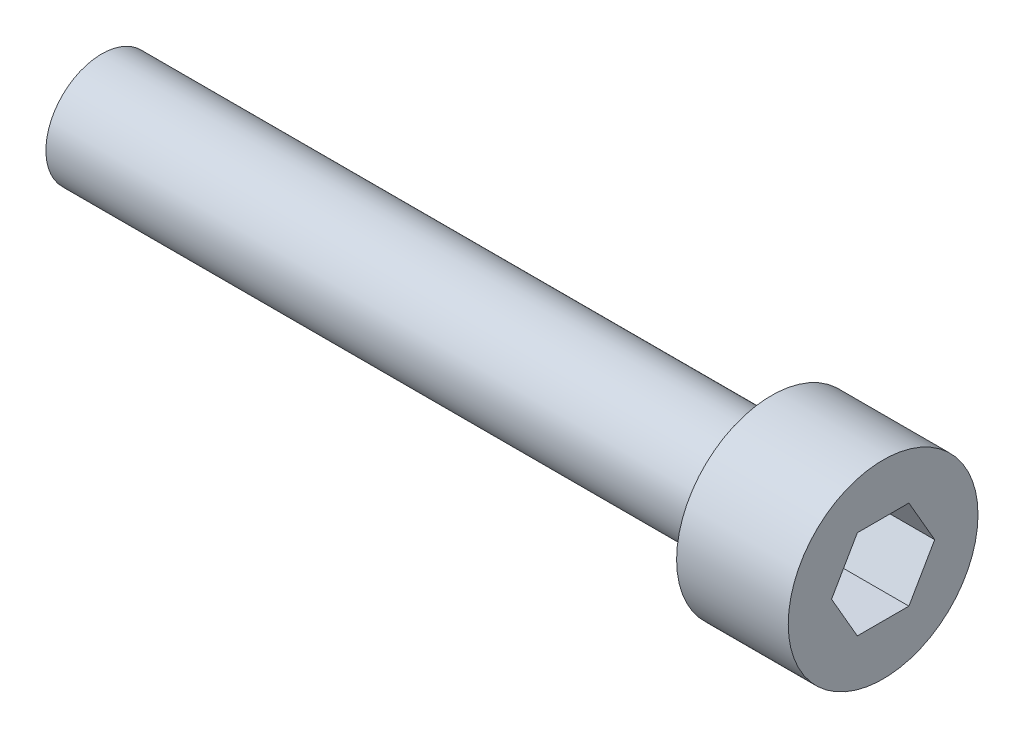
SolidWorks part; units mm, degrees
ref_plane "Plan de face" through (0, 0, 0) normal (0, 0, 1) x (1, 0, 0)
ref_plane "Plan de dessus" through (0, 0, 0) normal (0, 1, 0) x (1, 0, 0)
ref_plane "Plan de droite" through (0, 0, 0) normal (1, 0, 0) x (0, 0, -1)
sketch "Esquisse1" plane through (0, 0, 0) normal (1, 0, 0) x (0, 0, -1)
  circle A0 centre (0, 0) radius 2.5
  dimension "D1" = 5
extrude "Boss.-Extru.1" add sketch "Esquisse1" along normal blind 30
sketch "Esquisse2" plane through (30, 0, 0) normal (1, 0, 0) x (0, 0, -1)
  circle A0 centre (0, 0) radius 4.25
  dimension "D1" = 8.5
extrude "Boss.-Extru.2" add sketch "Esquisse2" along normal blind 5
sketch "Esquisse3" plane through (35, 0, 0) normal (1, 0, 0) x (0, 0, -1)
  line L1 (2.3094, 0) -> (1.1547, 2)
  line L2 (1.1547, 2) -> (-1.1547, 2)
  line L3 (-1.1547, 2) -> (-2.3094, 0)
  line L4 (-2.3094, 0) -> (-1.1547, -2)
  line L5 (-1.1547, -2) -> (1.1547, -2)
  line L6 (1.1547, -2) -> (2.3094, 0)
  circle A0 centre (0, 0) radius 2 construction
  dimension "D1" = 4
extrude "Enlèv. mat.-Extru.1" cut sketch "Esquisse3" against normal blind 3.5
